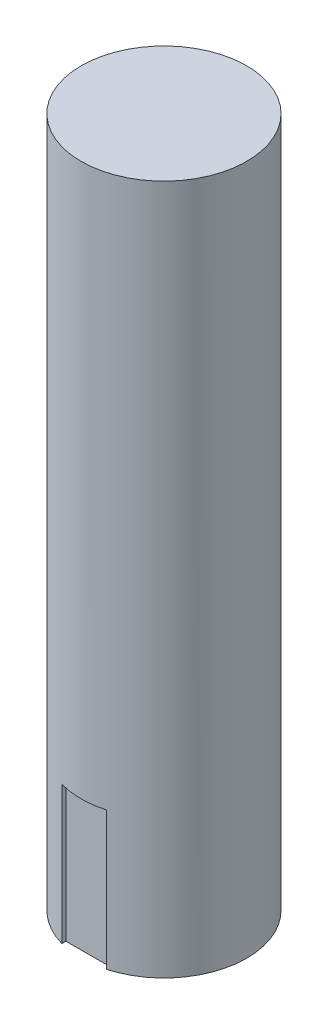
SolidWorks part; units mm, degrees
ref_plane "Front Plane" through (0, 0, 0) normal (0, 0, 1) x (1, 0, 0)
ref_plane "Top Plane" through (0, 0, 0) normal (0, 1, 0) x (1, 0, 0)
ref_plane "Right Plane" through (0, 0, 0) normal (1, 0, 0) x (0, 0, -1)
sketch "Sketch2" plane through (0, 0, 0) normal (0, 1, 0) x (1, 0, 0)
  circle A0 centre (0, 0) radius 30
  dimension "D1" = 60
extrude "Boss-Extrude1" add sketch "Sketch2" along normal mid plane 250
sketch "Sketch3" plane through (0, -125, 0) normal (0, -1, 0) x (1, 0, 0)
  line L0 (0, 0) -> (0, 30.92) construction
  line L1 (-10.394, 0) -> (-10.394, 36.9287)
  line L2 (8.0953, 27.42) -> (-8.0953, 27.42)
  line L3 (8.0953, 27.42) -> (8.0953, 34.42)
  line L4 (8.0953, 34.42) -> (-8.0953, 34.42)
  line L5 (-8.0953, 27.42) -> (-8.0953, 34.42)
  line L6 (8.0953, 27.42) -> (-8.0953, 34.42) construction
  line L7 (8.0953, 34.42) -> (-8.0953, 27.42) construction
  line L8 (10.394, 0) -> (10.394, 36.9287)
  circle M4 centre (0, 0) radius 30
  dimension "D1" = 30.92
  dimension "D2" = 7
extrude "Cut-Extrude1" cut sketch "Sketch3" against normal blind 50 contours L5 L3 L4 M4 | L5 L2 L3 M4
